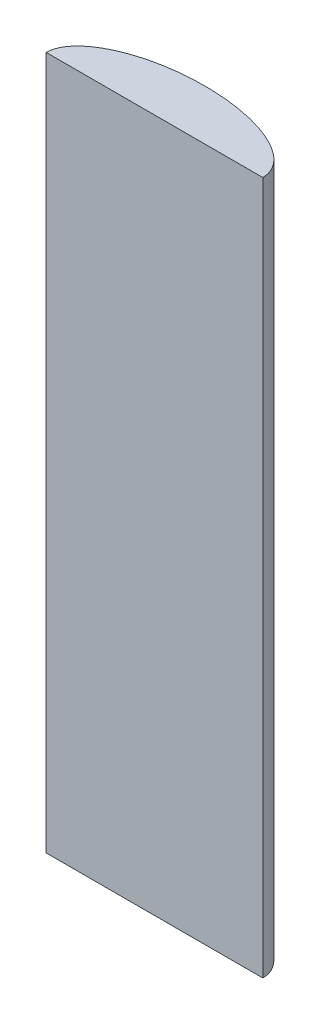
SolidWorks part; units mm, degrees
ref_plane "Front Plane" through (0, 0, 0) normal (0, 0, 1) x (1, 0, 0)
ref_plane "Top Plane" through (0, 0, 0) normal (0, 1, 0) x (1, 0, 0)
ref_plane "Right Plane" through (0, 0, 0) normal (1, 0, 0) x (0, 0, -1)
sketch "Sketch1" plane through (0, 0, 0) normal (0, 1, 0) x (1, 0, 0)
  line L0 (0, 0) -> (254, 0)
  ellipse E0 centre (127, 0) end of major axis (254, 0) minor radius 58.994 (254, 0) -> (0, 0) ccw
extrude "Boss-Extrude1" add sketch "Sketch1" along normal blind 812.8
sketch "Sketch2" plane through (0, 0, 0) normal (0, -1, 0) x (1, 0, 0)
  line L0 (127, 0) -> (127, -58.994) construction
  line L1 (0, 0) -> (254, 0) construction
  ellipse E0 centre (127, 0) end of major axis (254, 0) minor radius 58.994 (0, 0) -> (254, 0) ccw construction
sketch "Sketch3" plane through (0, 812.8, 0) normal (0, 1, 0) x (1, 0, 0)
  line L0 (127, 0) -> (127, 58.994) construction
  line L1 (0, 0) -> (254, 0) construction
